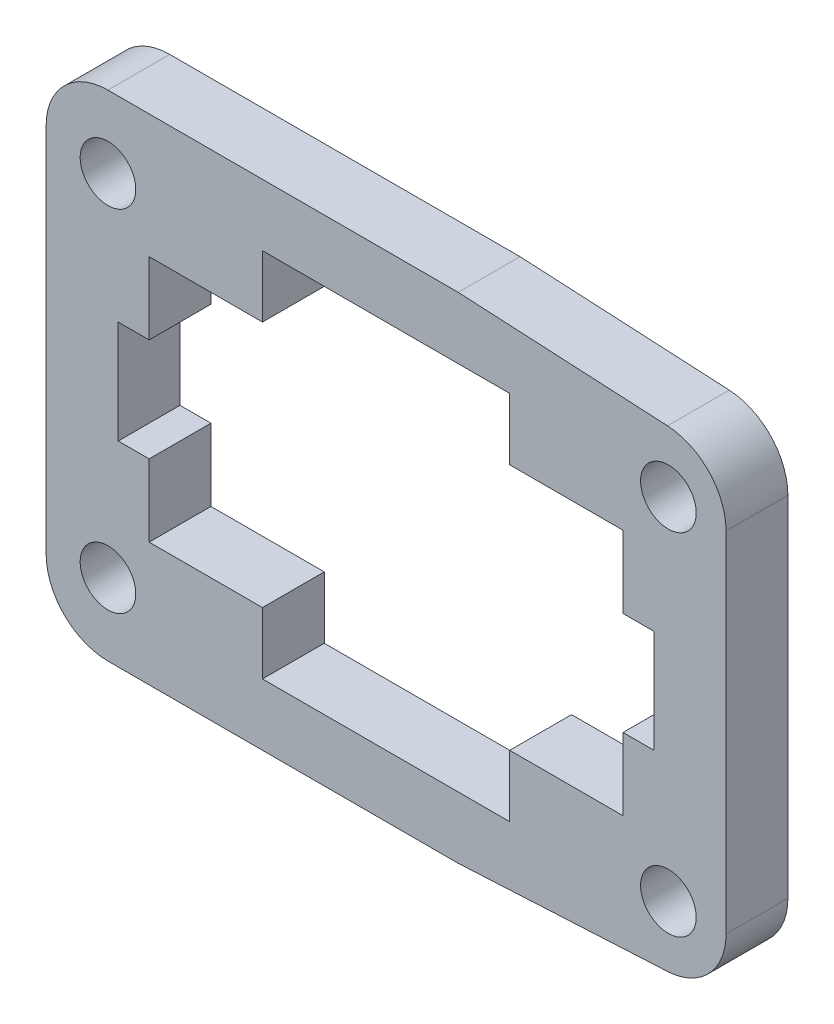
SolidWorks part; units mm, degrees
ref_plane "前视基准面" through (0, 0, 0) normal (0, 0, 1) x (1, 0, 0)
ref_plane "上视基准面" through (0, 0, 0) normal (0, 1, 0) x (1, 0, 0)
ref_plane "右视基准面" through (0, 0, 0) normal (1, 0, 0) x (0, 0, -1)
ref_plane "基准面1" through (0, 0, 3) normal (0, 0, 1) x (1, 0, 0)
sketch "草图1" plane through (0, 0, 3) normal (0, 0, 1) x (1, 0, 0)
  line L0 (23.3435, 9.5) -> (21.8432, 9.5)
  line L1 (21.8432, 9.5) -> (21.8432, 6)
  line L2 (21.8432, 6) -> (16.3434, 6)
  line L3 (16.3434, 6) -> (16.3434, 3)
  line L4 (16.3434, 3) -> (4.3434, 3)
  line L5 (4.3434, 3) -> (4.3434, 6)
  line L6 (4.3434, 6) -> (-1.1565, 6)
  line L7 (-1.1565, 6) -> (-1.1565, 9.5)
  line L8 (-1.1565, 9.5) -> (-2.6568, 9.5)
  line L9 (-2.6568, 9.5) -> (-2.6568, 14.4995)
  line L10 (-2.6568, 14.4995) -> (-1.1565, 14.4995)
  line L11 (-1.1565, 14.4995) -> (-1.1565, 17.9998)
  line L12 (-1.1565, 17.9998) -> (4.3434, 17.9998)
  line L13 (4.3434, 17.9998) -> (4.3434, 20.9998)
  line L14 (4.3434, 20.9998) -> (16.3434, 20.9998)
  line L15 (16.3434, 20.9998) -> (16.3434, 17.9998)
  line L16 (16.3434, 17.9998) -> (21.8432, 17.9998)
  line L17 (21.8432, 17.9998) -> (21.8432, 14.4995)
  line L18 (21.8432, 14.4995) -> (23.3435, 14.4995)
  line L19 (23.3435, 14.4995) -> (23.3435, 9.5)
  line L20 (-6.1571, 20.9998) -> (-6.1571, 3)
  line L21 (-3.1571, 0) -> (13.8437, 0)
  line L22 (13.8437, 0) -> (24.0014, 0.533)
  line L23 (26.8442, 3.5289) -> (26.8442, 20.4719)
  line L24 (24.0011, 23.4678) -> (13.8437, 23.9998)
  line L25 (13.8437, 23.9998) -> (-3.1571, 23.9998)
  circle A0 centre (-3.156, 20.4984) radius 1.35
  circle A1 centre (24.044, 20.4984) radius 1.35
  circle A2 centre (-3.156, 3.5011) radius 1.35
  circle A3 centre (24.044, 3.5011) radius 1.35
  arc A4 (-6.1571, 3) -> (-3.1571, 0) centre (-3.1571, 3) ccw
  arc A5 (24.0014, 0.533) -> (26.8442, 3.5289) centre (23.8442, 3.5289) ccw
  arc A6 (26.8442, 20.4719) -> (24.0011, 23.4678) centre (23.8442, 20.4719) ccw
  arc A7 (-3.1571, 23.9998) -> (-6.1571, 20.9998) centre (-3.1571, 20.9998) ccw
extrude "凸台-拉伸1" add sketch "草图1" against normal blind 3
